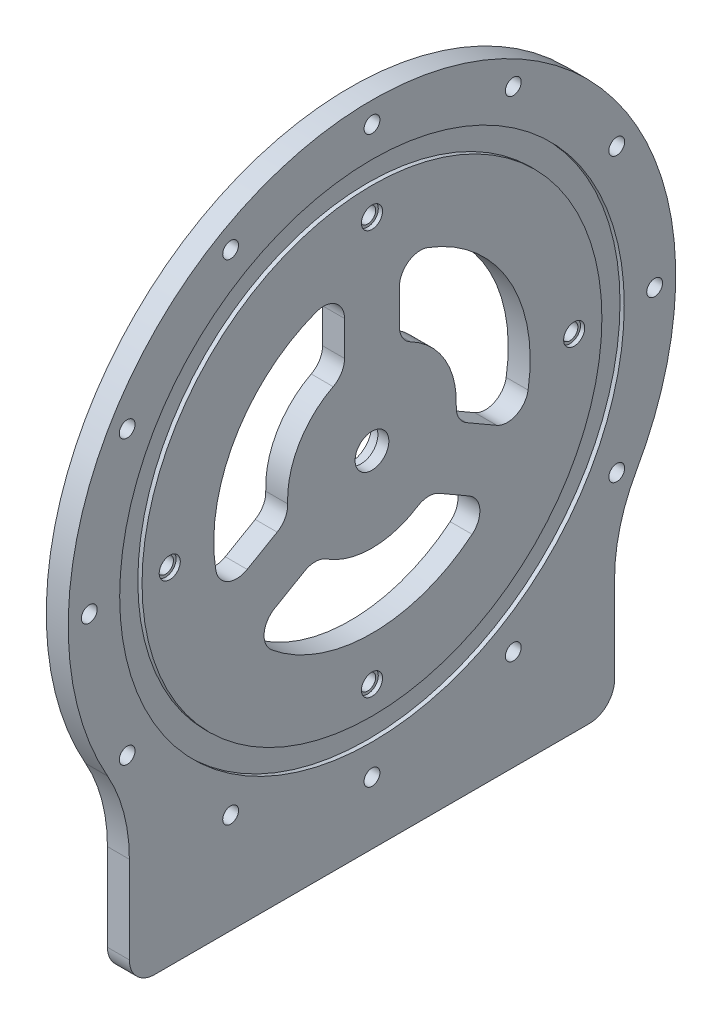
SolidWorks part; units mm, degrees
material "6061 Alloy"
ref_plane "Front Plane" through (0, 0, 0) normal (0, 0, 1) x (1, 0, 0)
ref_plane "Top Plane" through (0, 0, 0) normal (0, 1, 0) x (1, 0, 0)
ref_plane "Right Plane" through (0, 0, 0) normal (1, 0, 0) x (0, 0, -1)
sketch "Sketch1" plane through (0, 0, 0) normal (1, 0, 0) x (0, 0, -1)
  line L0 (0, -1000) -> (0, 49000) construction
  line L1 (5.5562, 0) -> (2.7781, 4.8119) construction
  line L2 (2.7781, 4.8119) -> (-2.7781, 4.8119) construction
  line L3 (-2.7781, 4.8119) -> (-5.5562, 0) construction
  line L4 (-5.5562, 0) -> (-2.7781, -4.8119) construction
  line L5 (-2.7781, -4.8119) -> (2.7781, -4.8119) construction
  line L6 (2.7781, -4.8119) -> (5.5562, 0) construction
  line L7 (-65.405, -103.8551) -> (65.405, -103.8551)
  line L8 (-73.025, -96.2351) -> (-73.025, -69.997)
  line L10 (73.025, -96.2351) -> (73.025, -69.997)
  circle A0 centre (0, 0) radius 69.85 construction
  circle A1 centre (0, 0) radius 76.2 construction
  circle A2 centre (0, 0) radius 5.08
  circle A3 centre (0, 0) radius 3.9688 construction
  arc A4 (79.6018, -44.9981) -> (-79.6018, -44.9981) centre (0, 0) ccw
  circle A5 centre (0, 0) radius 11.5094 construction
  circle A6 centre (0, 0) radius 91.44 construction
  arc A7 (65.405, -103.8551) -> (73.025, -96.2351) centre (65.405, -96.2351) ccw
  arc A8 (-65.405, -103.8551) -> (-73.025, -96.2351) centre (-65.405, -96.2351) cw
  arc A9 (79.6018, -44.9981) -> (73.025, -69.997) centre (123.825, -69.997) ccw
  arc A10 (-73.025, -69.997) -> (-79.6018, -44.9981) centre (-123.825, -69.997) ccw
  point P19 (73.025, -103.8551)
  point P26 (-73.025, -103.8551)
  dimension "D1" = 152.4
  dimension "D2" = 139.7
  dimension "D3" = 10.16
  dimension "D4" = 7.9375
  dimension "D5" = 15.24
  dimension "D6" = 23.0188
  dimension "D8" = 7.62
  dimension "D9" = 50.8
  dimension "D7" = 146.05
extrude "Boss-Extrude1" add sketch "Sketch1" along normal blind 6.604
sketch "Sketch2" plane through (0, 0, 0) normal (1, 0, 0) x (0, 0, -1)
  circle A0 centre (0, 0) radius 6.35 construction
  circle A1 centre (0, 0) radius 6.477
  dimension "D1" = 12.7
  dimension "D2" = 12.954
extrude "Cut-Extrude1" cut sketch "Sketch2" along direction (1, 0, 0) on the side of the normal blind 3.302
sketch "Sketch3" plane through (6.604, 0, 0) normal (1, 0, 0) x (0, 0, -1)
  circle A0 centre (0, 0) radius 75.946
  circle A1 centre (0, 0) radius 69.215
  dimension "D2" = 138.43
  dimension "D1" = 6.731
extrude "Cut-Extrude2" cut sketch "Sketch3" against normal blind 1.27
sketch "Sketch4" plane through (0, 0, 0) normal (-1, 0, 0) x (0, 0, 1)
  line L0 (0, -1000) -> (0, 49000) construction
  line L1 (-1000, 0) -> (49000, 0) construction
  circle A1 centre (0, 85.09) radius 2.3812
  circle A3 centre (0, 0) radius 85.09 construction
  circle A4 centre (42.545, 73.6901) radius 2.3812
  circle A5 centre (73.6901, 42.545) radius 2.3813
  circle A6 centre (85.09, 0) radius 2.3813
  circle A7 centre (73.6901, -42.545) radius 2.3813
  circle A8 centre (42.545, -73.6901) radius 2.3812
  circle A9 centre (0, -85.09) radius 2.3812
  circle A10 centre (-42.545, -73.6901) radius 2.3812
  circle A11 centre (-73.6901, -42.545) radius 2.3813
  circle A12 centre (-85.09, 0) radius 2.3813
  circle A13 centre (-73.6901, 42.545) radius 2.3813
  circle A14 centre (-42.545, 73.6901) radius 2.3812
  point P34 (0, 0)
  dimension "D2" = 12
extrude "Cut-Extrude3" cut sketch "Sketch4" against normal through all
sketch "Sketch5" plane through (0, 0, 0) normal (-1, 0, 0) x (0, 0, 1)
  circle A0 centre (0, 85.09) radius 3.7783
  circle A3 centre (42.545, 73.6901) radius 3.7783
  circle A5 centre (-42.545, 73.6901) radius 3.7783
  circle A6 centre (73.6901, 42.545) radius 3.7783
  circle A7 centre (85.09, 0) radius 3.7783
  circle A8 centre (73.6901, -42.545) radius 3.7783
  circle A9 centre (42.545, -73.6901) radius 3.7783
  circle A10 centre (0, -85.09) radius 3.7783
  circle A11 centre (-42.545, -73.6901) radius 3.7783
  circle A12 centre (-73.6901, -42.545) radius 3.7783
  circle A13 centre (-85.09, 0) radius 3.7783
  circle A14 centre (-73.6901, 42.545) radius 3.7783
  point P29 (0, 0)
  dimension "D1" = 12
extrude "Cut-Extrude4" cut sketch "Sketch5" against normal blind 1.27
sketch "Sketch6" plane through (0, 0, 0) normal (-1, 0, 0) x (0, 0, 1)
  line L0 (-1000, 0) -> (49000, 0) construction
  line L1 (0, 0) -> (25000, 43301.2702) construction
  line L2 (0, 0) -> (25000, -43301.2702) construction
  circle A0 centre (0, 0) radius 25.4 construction
  circle A1 centre (-19.0117, 0) radius 2.3813
  circle A2 centre (-9.5059, 16.4647) radius 2.3813
  circle A3 centre (9.5059, 16.4647) radius 2.3812
  circle A4 centre (19.0117, 0) radius 2.3813
  circle A5 centre (9.5059, -16.4647) radius 2.3813
  circle A6 centre (-9.5059, -16.4647) radius 2.3813
  point P19 (0, 0)
  dimension "D1" = 6
  dimension "D2" = 50.8
  dimension "D3" = 4.7625
  dimension "D4" = 19.0117
sketch "Sketch9" plane through (0, 0, 0) normal (-1, 0, 0) x (0, 0, 1)
  line L0 (0, 0) -> (0, 138.31) construction
  line L1 (0, 0) -> (103.2188, -59.5934) construction
  line L2 (0, 0) -> (-103.0172, -59.477) construction
  line L5 (-8.255, 38.6047) -> (-8.255, 28.1914)
  line L7 (8.255, 38.6047) -> (8.255, 28.1914)
  line L8 (37.5601, -12.1533) -> (28.542, -6.9467)
  line L10 (29.3051, -26.4514) -> (20.287, -21.2448)
  line L12 (-29.3051, -26.4514) -> (-20.287, -21.2448)
  line L14 (-37.5601, -12.1533) -> (-28.542, -6.9467)
  arc A0 (-8.255, 24.0211) -> (-24.9304, -4.8615) centre (0, 0) ccw construction
  arc A1 (-16.8519, 44.5438) -> (-47.0021, -7.6777) centre (0, 0) ccw
  arc A2 (-11.684, 22.5531) -> (-25.3736, -1.1579) centre (0, 0) ccw
  arc A3 (24.9304, -4.8615) -> (8.255, 24.0211) centre (0, 0) ccw construction
  arc A4 (25.3736, -1.1579) -> (11.684, 22.5531) centre (0, 0) ccw
  arc A5 (47.0021, -7.6777) -> (16.8519, 44.5438) centre (0, 0) ccw
  arc A6 (-16.6754, -19.1596) -> (16.6754, -19.1596) centre (0, 0) ccw construction
  arc A7 (-13.6896, -21.3952) -> (13.6896, -21.3952) centre (0, 0) ccw
  arc A8 (-30.1501, -36.8661) -> (30.1501, -36.8661) centre (0, 0) ccw
  arc A9 (-16.8519, 44.5438) -> (-8.255, 38.6047) centre (-14.605, 38.6047) cw
  arc A10 (-8.255, 28.1914) -> (-11.684, 22.5531) centre (-14.605, 28.1914) cw
  arc A11 (-25.3736, -1.1579) -> (-28.542, -6.9467) centre (-31.717, -1.4474) cw
  arc A12 (-47.0021, -7.6777) -> (-37.5601, -12.1533) centre (-40.7351, -6.654) ccw
  arc A13 (-30.1501, -36.8661) -> (-29.3051, -26.4514) centre (-26.1301, -31.9506) cw
  arc A14 (-20.287, -21.2448) -> (-13.6896, -21.3952) centre (-17.112, -26.744) cw
  arc A15 (13.6896, -21.3952) -> (20.287, -21.2448) centre (17.112, -26.744) cw
  arc A16 (30.1501, -36.8661) -> (29.3051, -26.4514) centre (26.1301, -31.9506) ccw
  arc A17 (47.0021, -7.6777) -> (37.5601, -12.1533) centre (40.7351, -6.654) cw
  arc A18 (28.542, -6.9467) -> (25.3736, -1.1579) centre (31.717, -1.4474) cw
  arc A19 (16.8519, 44.5438) -> (8.255, 38.6047) centre (14.605, 38.6047) ccw
  arc A20 (11.684, 22.5531) -> (8.255, 28.1914) centre (14.605, 28.1914) cw
  point P24 (0, 0)
  dimension "D1" = 120
  dimension "D3" = 95.25
  dimension "D4" = 50.8
  dimension "D7" = 6.35
  dimension "D2" = 120
  dimension "D5" = 16.51
  dimension "D6" = 3
extrude "Cut-Extrude5" cut sketch "Sketch9" against normal through all
sketch "Sketch10" plane through (0, 0, 0) normal (-1, 0, 0) x (0, 0, 1)
  circle A0 centre (0, 0) radius 50.8
  circle A1 centre (0, 0) radius 57.15
extrude "Cut-Extrude6" cut sketch "Sketch10" against normal blind 1.27
sketch "Sketch12" plane through (0, 0, 0) normal (-1, 0, 0) x (0, 0, 1)
  circle A0 centre (0, 60.8743) radius 2.3813
  circle A1 centre (60.8743, 0) radius 2.3813
  circle A2 centre (0, -60.8743) radius 2.3813
  circle A3 centre (-60.8743, 0) radius 2.3813
  point P13 (0, 0)
  point P33 (0, 0)
  dimension "D1" = 4
extrude "Cut-Extrude7" cut sketch "Sketch12" against normal through all
sketch "Sketch15" plane through (6.604, 0, 0) normal (1, 0, 0) x (0, 0, -1)
  circle A0 centre (0, 60.8743) radius 3.175
  circle A1 centre (60.8743, 0) radius 3.175
  circle A2 centre (0, -60.8743) radius 3.175
  circle A3 centre (-60.8743, 0) radius 3.175
  point P12 (0, 0)
  dimension "D1" = 4
extrude "Cut-Extrude11" cut sketch "Sketch15" against normal blind 1.27
